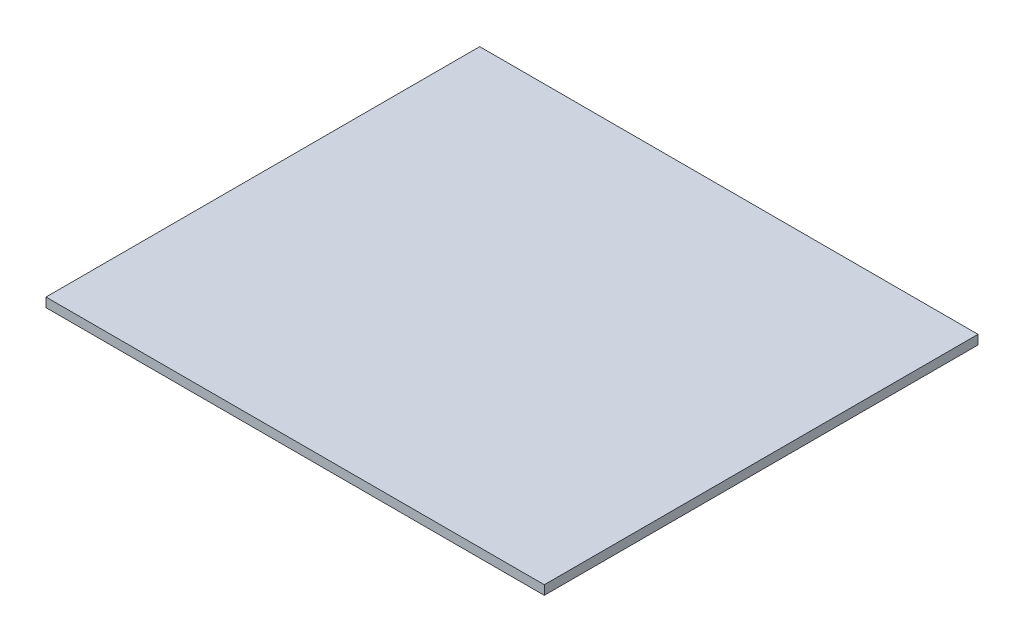
SolidWorks part; units mm, degrees
material "ABS"
ref_plane "Ebene vorne" through (0, 0, 0) normal (0, 0, 1) x (1, 0, 0)
ref_plane "Ebene oben" through (0, 0, 0) normal (0, 1, 0) x (1, 0, 0)
ref_plane "Ebene rechts" through (0, 0, 0) normal (1, 0, 0) x (0, 0, -1)
sketch "Skizze1" plane through (0, 0, 0) normal (0, 1, 0) x (1, 0, 0)
  line L1 (-135, 117.5) -> (135, 117.5)
  line L2 (-135, 117.5) -> (-135, -117.5)
  line L3 (-135, -117.5) -> (135, -117.5)
  line L4 (135, 117.5) -> (135, -117.5)
  line L5 (-135, 117.5) -> (135, -117.5) construction
  line L6 (-135, -117.5) -> (135, 117.5) construction
  point P0 (0, 0)
  dimension "D1" = 270
  dimension "D2" = 235
extrude "Aufsatz-Linear austragen1" add sketch "Skizze1" along normal blind 5
